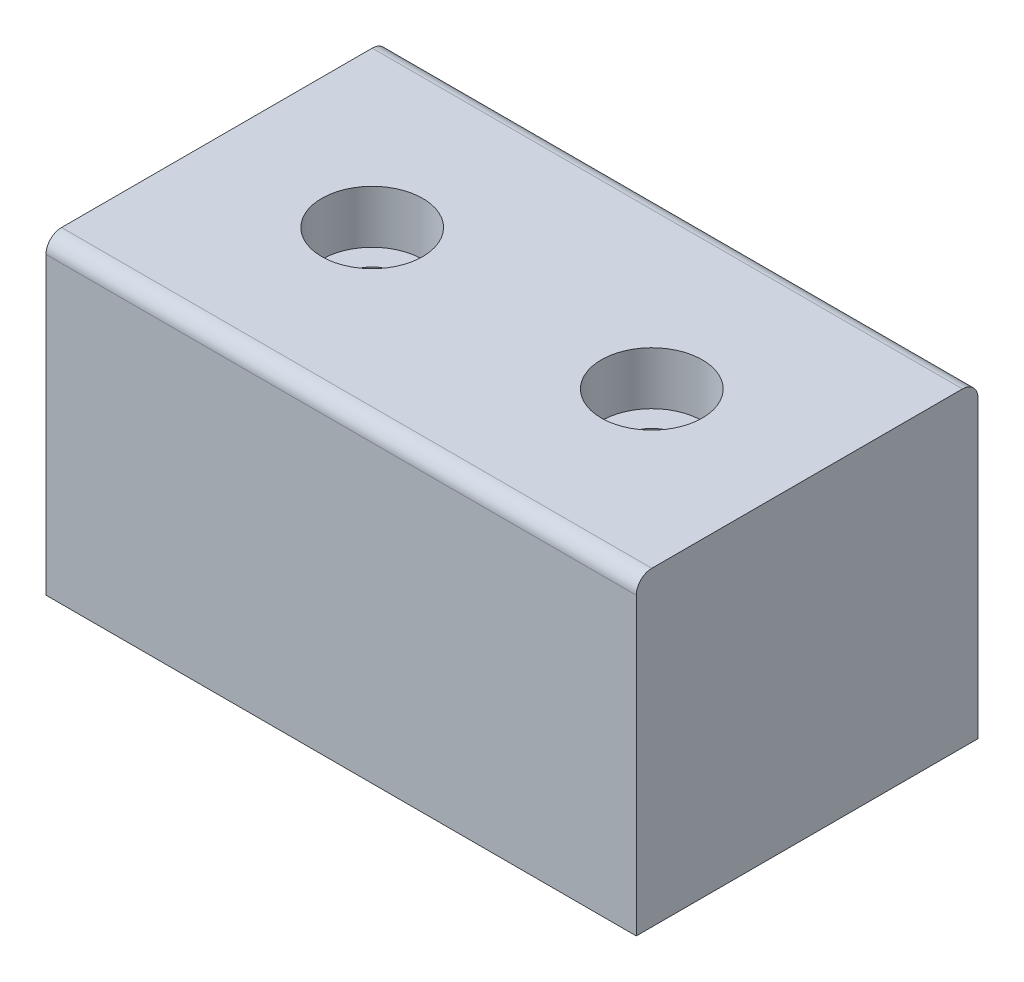
SolidWorks part; units mm, degrees
ref_plane "Face" through (0, 0, 0) normal (0, 0, 1) x (1, 0, 0)
ref_plane "Dessus" through (0, 0, 0) normal (0, 1, 0) x (1, 0, 0)
ref_plane "Droite" through (0, 0, 0) normal (1, 0, 0) x (0, 0, -1)
sketch "Esquisse2" plane through (0, 0, 0) normal (0, 1, 0) x (1, 0, 0)
  line L1 (-19, 11) -> (19, 11)
  line L2 (-19, 11) -> (-19, -11)
  line L3 (-19, -11) -> (19, -11)
  line L4 (19, 11) -> (19, -11)
  dimension "D1" = 11
  dimension "D2" = 22
  dimension "D3" = 19
  dimension "D4" = 38
extrude "Boss.-Extru.1" add sketch "Esquisse2" along normal blind 20
sketch "Esquisse3" plane through (0, 20, 0) normal (0, 1, 0) x (1, 0, 0)
  line L0 (-19, 0) -> (19, 0) construction
  line L1 (-19, 11) -> (-19, -11) construction
  line L2 (19, -11) -> (19, 11) construction
  line L3 (-9, 11) -> (-9, -11) construction
  line L4 (19, 11) -> (-19, 11) construction
  line L5 (-19, -11) -> (19, -11) construction
  line L6 (9, 11) -> (9, -11) construction
  dimension "D1" = 9
  dimension "D2" = 9
hole_wizard "Chambrage pour vis à tête hexagonale M31" positions "Esquisse5" profile "Esquisse4" counterbore size "M3" standard "Iso" end condition through all
sketch "Esquisse5" plane through (0, 20, 0) normal (0, 1, 0) x (1, 0, 0)
  line L0 (-9, 11) -> (-9, -11) construction
  line L1 (9, 11) -> (9, -11) construction
  point P0 (-9, 0)
  point P4 (9, 0)
sketch "Esquisse4" plane through (-9, 20, 0) normal (1, 0, 0) x (0, 0, 1)
  line L0 (0, 0) -> (0, 20)
  line L1 (0, 20) -> (1.7, 20)
  line L3 (1.7, 20) -> (1.7, 3.4)
  line L4 (1.7, 3.4) -> (3.25, 3.4)
  line L5 (3.25, 3.4) -> (3.25, 0)
  line L7 (3.25, 0) -> (0, 0)
  line L11 (0, -6.35) -> (0, 107.95) construction
  dimension "Diamètre du perçage jusqu'au prochain" = 3.4
  dimension "Profondeur du perçage jusqu'au prochain" = 20
  dimension "Diamètre du chambrage" = 6.5
  dimension "Profondeur du chambrage" = 3.4
fillet "Congé1" radius 1 2 edges at (0, 20, -11) (0, 20, 11)
